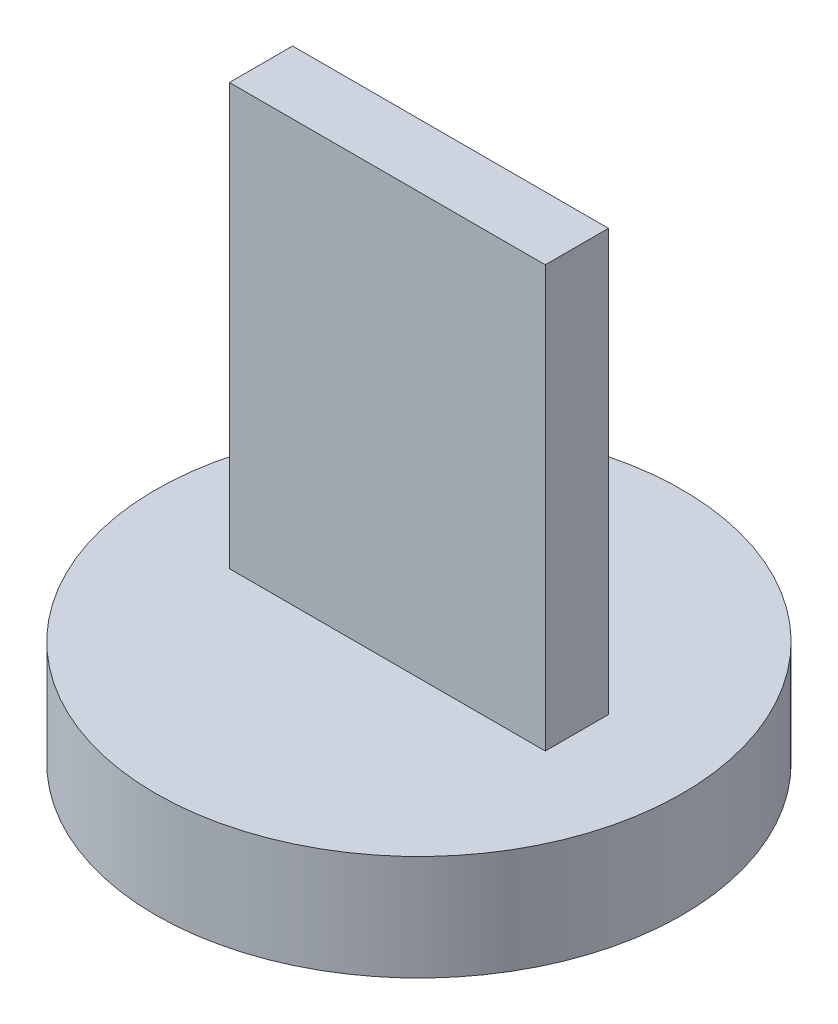
SolidWorks part; units mm, degrees
ref_plane "Vorne" through (0, 0, 0) normal (0, 0, 1) x (1, 0, 0)
ref_plane "Oben" through (0, 0, 0) normal (0, 1, 0) x (1, 0, 0)
ref_plane "Rechts" through (0, 0, 0) normal (1, 0, 0) x (0, 0, -1)
sketch "Skizze1" plane through (0, 0, 0) normal (0, 1, 0) x (1, 0, 0)
  circle A0 centre (0, 0) radius 2.5
  dimension "D1" = 5
extrude "Aufsatz-Linear austragen1" add sketch "Skizze1" along normal blind 1
sketch "Skizze2" plane through (0, 1, 0) normal (0, 1, 0) x (1, 0, 0)
  line L0 (1.5, 0.3) -> (1.5, -0.3)
  line L1 (1.5, 0.3) -> (-1.5, 0.3)
  line L2 (1.5, -0.3) -> (-1.5, -0.3)
  line L3 (-1.5, 0.3) -> (-1.5, -0.3)
  line L4 (1.5, 0.3) -> (-1.5, -0.3) construction
  line L5 (1.5, -0.3) -> (-1.5, 0.3) construction
  line L6 (-0.55, 0) -> (0.55, 0) construction
  point P1 (0, 0)
  dimension "D1" = 0.6
  dimension "D2" = 3
extrude "Aufsatz-Linear austragen2" add sketch "Skizze2" along normal blind 4
